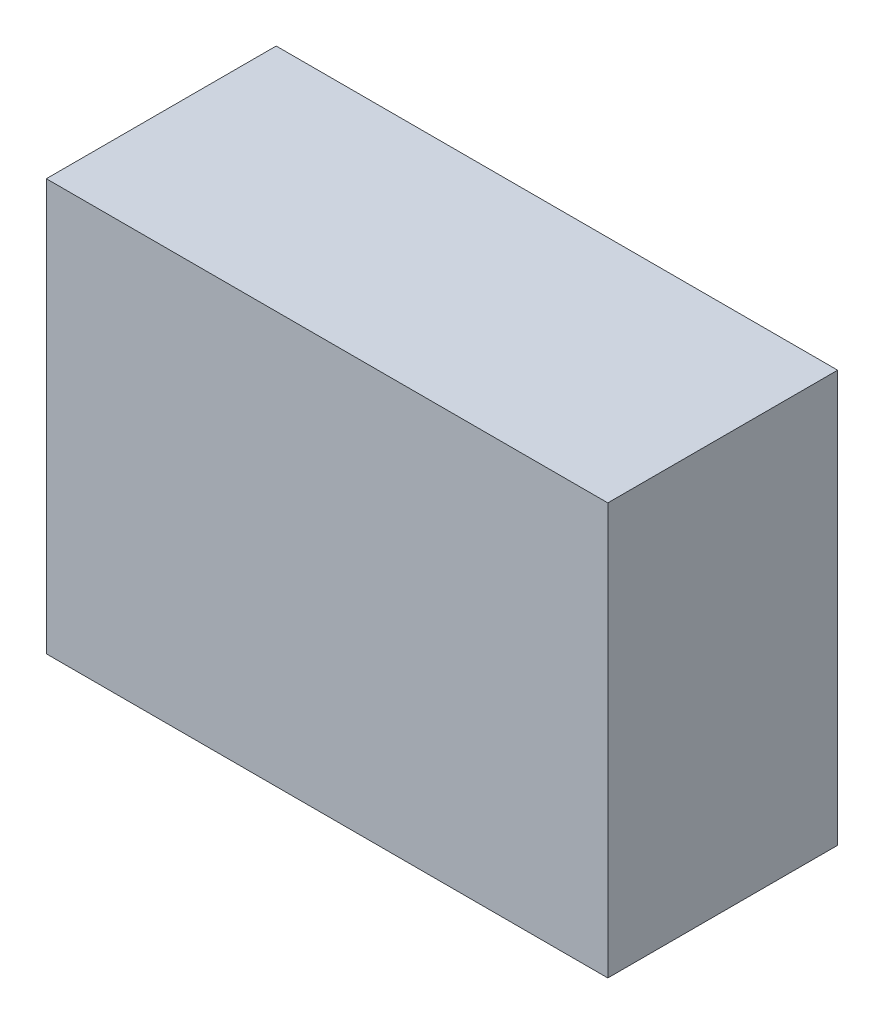
SolidWorks part; units mm, degrees
ref_plane "Front Plane" through (0, 0, 0) normal (0, 0, 1) x (1, 0, 0)
ref_plane "Top Plane" through (0, 0, 0) normal (0, 1, 0) x (1, 0, 0)
ref_plane "Right Plane" through (0, 0, 0) normal (1, 0, 0) x (0, 0, -1)
sketch "Sketch1" plane through (0, 0, 0) normal (0, 0, 1) x (1, 0, 0)
  line L1 (-32, -23.45) -> (32, -23.45)
  line L2 (-32, -23.45) -> (-32, 23.45)
  line L3 (-32, 23.45) -> (32, 23.45)
  line L4 (32, -23.45) -> (32, 23.45)
  line L5 (-32, -23.45) -> (32, 23.45) construction
  line L6 (-32, 23.45) -> (32, -23.45) construction
  point P0 (0, 0)
extrude "Envelope" add sketch "Sketch1" along normal blind 26.2
